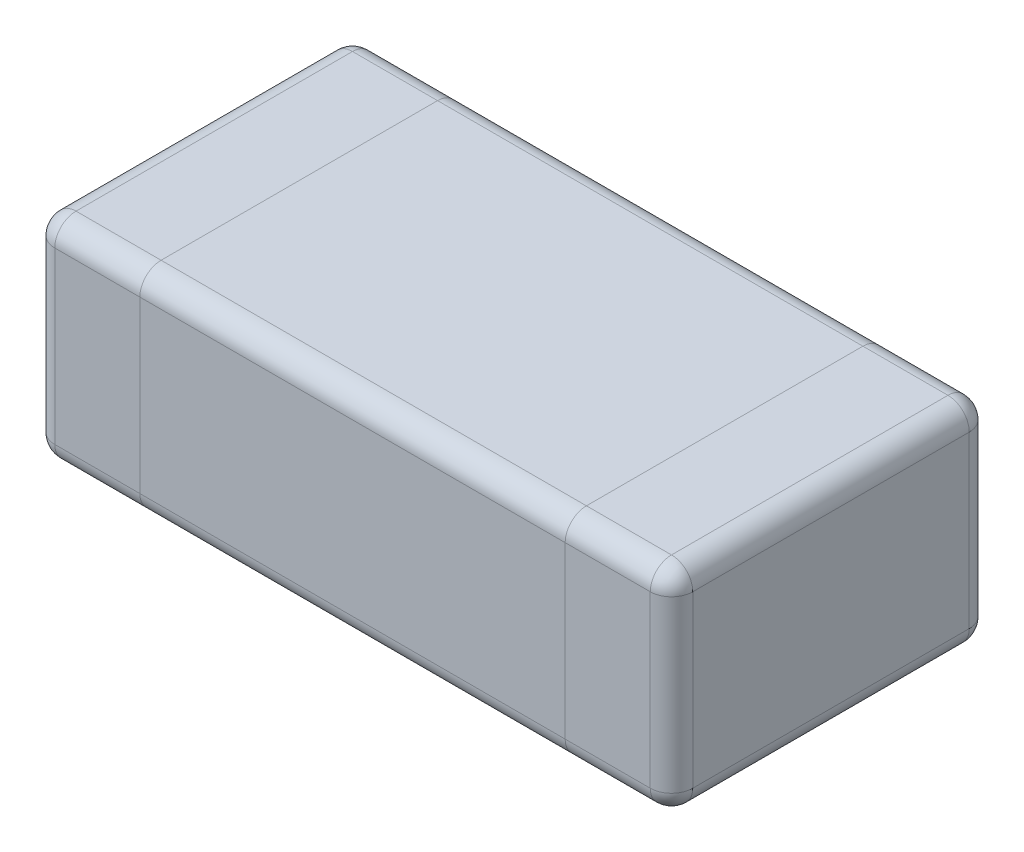
SolidWorks part; units mm, degrees
material "Ceramic Porcelain"
ref_plane "Front Plane" through (0, 0, 0) normal (0, 0, 1) x (1, 0, 0)
ref_plane "Top Plane" through (0, 0, 0) normal (0, 1, 0) x (1, 0, 0)
ref_plane "Right Plane" through (0, 0, 0) normal (1, 0, 0) x (0, 0, -1)
sketch "Sketch1" plane through (0, 0, 0) normal (0, 0, 1) x (1, 0, 0)
  line L1 (-0.2, 0.2) -> (0.2, 0.2)
  line L2 (-0.2, 0.2) -> (-0.2, 0)
  line L3 (-0.2, 0) -> (0.2, 0)
  line L4 (0.2, 0.2) -> (0.2, 0)
  dimension "D1" = 0.4
  dimension "D2" = 0.2
extrude "Boss-Extrude1" add sketch "Sketch1" along normal blind 0.3
fillet "Fillet1" radius 0.02 4 edges at (0, 0, 0) (0, 0, 0.3) (0, 0.2, 0) (0, 0.2, 0.3)
sketch "Sketch2" plane through (-0.2, 0, 0) normal (-1, 0, 0) x (0, 0, 1)
  line L8 (0, 0.18) -> (0, 0.02)
  line L9 (0.02, 0) -> (0.28, 0)
  line L10 (0.3, 0.02) -> (0.3, 0.18)
  line L11 (0.28, 0.2) -> (0.02, 0.2)
  line L12 (0, 0.18) -> (0, 0.02)
  line L13 (0.02, 0) -> (0.28, 0)
  line L14 (0.3, 0.02) -> (0.3, 0.18)
  line L15 (0.28, 0.2) -> (0.02, 0.2)
  arc A8 (0, 0.02) -> (0.02, 0) centre (0.02, 0.02) ccw
  arc A9 (0.28, 0) -> (0.3, 0.02) centre (0.28, 0.02) ccw
  arc A10 (0.3, 0.18) -> (0.28, 0.2) centre (0.28, 0.18) ccw
  arc A11 (0.02, 0.2) -> (0, 0.18) centre (0.02, 0.18) ccw
  arc A12 (0, 0.02) -> (0.02, 0) centre (0.02, 0.02) ccw
  arc A13 (0.28, 0) -> (0.3, 0.02) centre (0.28, 0.02) ccw
  arc A14 (0.3, 0.18) -> (0.28, 0.2) centre (0.28, 0.18) ccw
  arc A15 (0.02, 0.2) -> (0, 0.18) centre (0.02, 0.18) ccw
  dimension "D1" = 0
extrude "Boss-Extrude2" add sketch "Sketch2" along normal blind 0.1 separate body
fillet "Fillet2" radius 0.02 8 edges at (-0.3, 0.2, 0.15) (-0.3, 0.1941, 0.2941) (-0.3, 0.1, 0.3) (-0.3, 0.0059, 0.2941) (-0.3, 0, 0.15) (-0.3, 0.0059, 0.0059) (-0.3, 0.1, 0) (-0.3, 0.1941, 0.0059)
mirror "Mirror1" about plane through (0, 0, 0) normal (1, 0, 0) of bodies 102
equation "\"L\" = 0.6"
equation "\"W\"= 0.3"
equation "\"H\"= 0.2"
equation "\"e\"= 0.1"
equation "\"D1@Sketch1\"=\"L\"-\"e\"*2"
equation "\"D2@Sketch1\"=\"H\""
equation "\"D1@Boss-Extrude1\"=\"W\""
equation "\"D1@Fillet1\"=\"e\"/5"
equation "\"D1@Boss-Extrude2\"=\"e\""
equation "\"D1@Fillet2\"=\"e\"/5"
